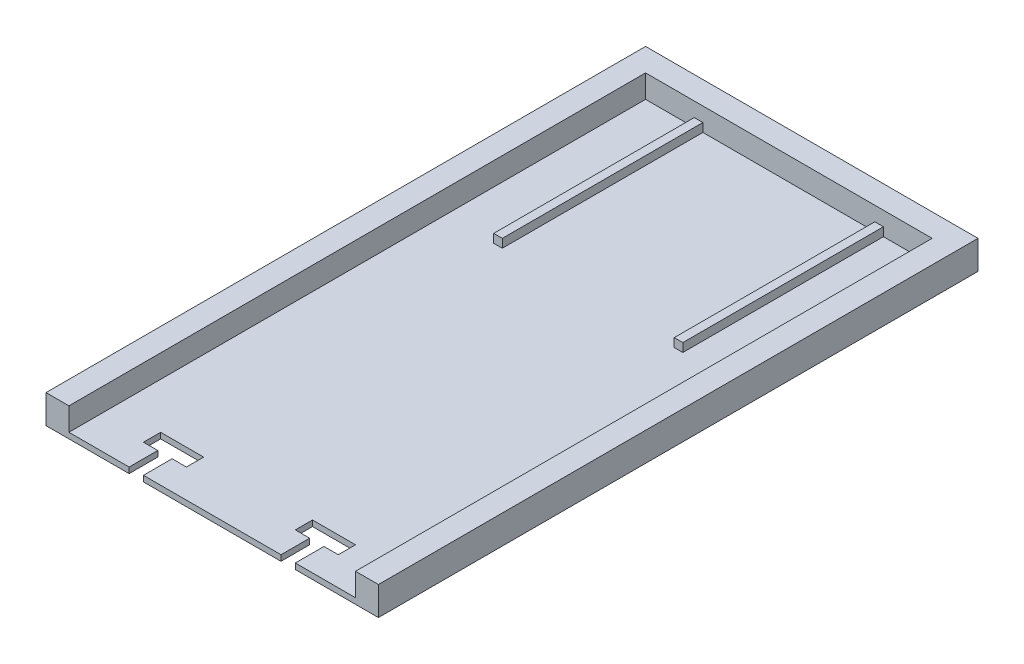
SolidWorks part; units mm, degrees
ref_plane "Front Plane" through (0, 0, 0) normal (0, 0, 1) x (1, 0, 0)
ref_plane "Top Plane" through (0, 0, 0) normal (0, 1, 0) x (1, 0, 0)
ref_plane "Right Plane" through (0, 0, 0) normal (1, 0, 0) x (0, 0, -1)
sketch "Sketch3" plane through (0, 0, 0) normal (0, 1, 0) x (1, 0, 0)
  line L0 (-1156.1049, 777.2674) -> (-1040.1049, 777.2674)
  line L1 (-1040.1049, 777.2674) -> (-1040.1049, 361.2674)
  line L2 (-1040.1049, 361.2674) -> (-1156.1049, 361.2674)
  line L3 (-1156.1049, 361.2674) -> (-1156.1049, 777.2674)
extrude "Boss-Extrude1" add sketch "Sketch3" along normal blind 10
sketch "Sketch4" plane through (0, 10, 0) normal (0, 1, 0) x (1, 0, 0)
  line L4 (-1148.1049, 769.2674) -> (-1048.1049, 769.2674)
  line L5 (-1148.1049, 769.2674) -> (-1148.1049, 369.2674)
  line L6 (-1148.1049, 369.2674) -> (-1048.1049, 369.2674)
  line L7 (-1048.1049, 769.2674) -> (-1048.1049, 369.2674)
  dimension "D1" = 100
  dimension "D2" = 400
extrude "Cut-Extrude1" cut sketch "Sketch4" against normal blind 8
sketch "Sketch6" plane through (0, 2, 0) normal (0, 1, 0) x (1, 0, 0)
  line L1 (-1048.1049, 769.2674) -> (-1148.1049, 769.2674) construction
  line L2 (-1128.1049, 769.2674) -> (-1128.1049, 669.2674)
  line L3 (-1128.1049, 669.2674) -> (-1131.1049, 669.2674)
  line L4 (-1131.1049, 669.2674) -> (-1131.1049, 769.2674)
  line L5 (-1128.1049, 769.2674) -> (-1131.1049, 769.2674)
  line L7 (-1068.1049, 769.2674) -> (-1068.1049, 669.2674)
  line L8 (-1068.1049, 669.2674) -> (-1065.1049, 669.2674)
  line L9 (-1065.1049, 669.2674) -> (-1065.1049, 769.2674)
  line L10 (-1048.1049, 769.2674) -> (-1148.1049, 769.2674) construction
  line L11 (-1068.1049, 769.2674) -> (-1065.1049, 769.2674)
extrude "Boss-Extrude4" add sketch "Sketch6" along normal blind 3
sketch "Sketch7" plane through (0, 2, 0) normal (0, 1, 0) x (1, 0, 0)
  line L0 (-1068.1049, 669.2674) -> (-1085.4049, 669.2674)
  line L1 (-1068.1049, 769.2674) -> (-1068.1049, 669.2674) construction
  line L2 (-1068.1049, 769.2674) -> (-1068.1049, 669.2674) construction
  circle A0 centre (-1085.4049, 452.1683) radius 1.5
extrude "Boss-Extrude5" add sketch "Sketch7" along normal blind 3 contours A0
sketch "Sketch8" plane through (0, 2, 0) normal (0, 1, 0) x (1, 0, 0)
  line L0 (-1040.1049, 361.2674) -> (-1040.1049, 538.0477)
  line L1 (-1040.1049, 361.2674) -> (-1040.1049, 777.2674) construction
  line L2 (-1040.1049, 538.0477) -> (-1156.1049, 538.0477)
  line L3 (-1156.1049, 777.2674) -> (-1156.1049, 361.2674) construction
  line L4 (-1156.1049, 538.0477) -> (-1156.1049, 361.2674)
  line L5 (-1156.1049, 361.2674) -> (-1040.1049, 361.2674) construction
  line L6 (-1156.1049, 361.2674) -> (-1040.1049, 361.2674)
extrude "Cut-Extrude2" cut sketch "Sketch8" against normal blind 10 and the other way blind 10
sketch "Sketch9" plane through (0, 2, 0) normal (0, 1, 0) x (1, 0, 0)
  line L0 (-1127.1049, 538.0477) -> (-1122.1049, 538.0477)
  line L1 (-1148.1049, 538.0477) -> (-1048.1049, 538.0477) construction
  line L2 (-1127.1049, 538.0477) -> (-1127.1049, 548.0477)
  line L3 (-1127.1049, 548.0477) -> (-1132.1049, 548.0477)
  line L4 (-1132.1049, 548.0477) -> (-1132.1049, 554.0477)
  line L6 (-1122.1049, 538.0477) -> (-1122.1049, 548.0477)
  line L7 (-1122.1049, 548.0477) -> (-1117.1049, 548.0477)
  line L8 (-1117.1049, 548.0477) -> (-1117.1049, 554.0477)
  line L9 (-1117.1049, 554.0477) -> (-1132.1049, 554.0477)
  line L10 (-1098.1049, 538.0477) -> (-1098.1049, 777.2674)
  line L11 (-1040.1049, 777.2674) -> (-1156.1049, 777.2674) construction
  line L12 (-1079.1049, 554.0477) -> (-1064.1049, 554.0477)
  line L13 (-1079.1049, 548.0477) -> (-1079.1049, 554.0477)
  line L14 (-1074.1049, 548.0477) -> (-1079.1049, 548.0477)
  line L15 (-1074.1049, 538.0477) -> (-1074.1049, 548.0477)
  line L16 (-1064.1049, 548.0477) -> (-1064.1049, 554.0477)
  line L17 (-1069.1049, 548.0477) -> (-1064.1049, 548.0477)
  line L18 (-1069.1049, 538.0477) -> (-1069.1049, 548.0477)
  line L19 (-1069.1049, 538.0477) -> (-1074.1049, 538.0477)
  line M2 (-1148.1049, 538.0477) -> (-1048.1049, 538.0477)
extrude "Cut-Extrude4" cut sketch "Sketch9" against normal blind 37 contours L8 L9 L4 L3 L2 L6 L7 M2 | L18 L17 L16 L12 L13 L14 L15 M2
sketch "Sketch10" plane through (0, 5, 0) normal (0, 1, 0) x (1, 0, 0)
  line L0 (-1156.1049, 538.0477) -> (-1156.1049, 568.0477)
  line L1 (-1156.1049, 777.2674) -> (-1156.1049, 538.0477) construction
  line L2 (-1069.1049, 568.0477) -> (-1074.1049, 568.0477)
  line L3 (-1040.1049, 538.0477) -> (-1040.1049, 777.2674) construction
  line L4 (-1079.1049, 584.0477) -> (-1064.1049, 584.0477)
  line L5 (-1127.1049, 568.0477) -> (-1127.1049, 578.0477)
  line L6 (-1127.1049, 578.0477) -> (-1132.1049, 578.0477)
  line L7 (-1132.1049, 578.0477) -> (-1132.1049, 584.0477)
  line L8 (-1079.1049, 578.0477) -> (-1079.1049, 584.0477)
  line L9 (-1122.1049, 568.0477) -> (-1122.1049, 578.0477)
  line L10 (-1122.1049, 578.0477) -> (-1117.1049, 578.0477)
  line L11 (-1117.1049, 578.0477) -> (-1117.1049, 584.0477)
  line L12 (-1117.1049, 584.0477) -> (-1132.1049, 584.0477)
  line L13 (-1156.1049, 568.0477) -> (-1040.1049, 568.0477)
  line L14 (-1156.1049, 568.0477) -> (-1156.1049, 538.0477)
  line L15 (-1040.1049, 538.0477) -> (-1040.1049, 568.0477)
  line L16 (-1156.1049, 538.0477) -> (-1040.1049, 538.0477)
  line L17 (-1074.1049, 578.0477) -> (-1079.1049, 578.0477)
  line L18 (-1127.1049, 568.0477) -> (-1122.1049, 568.0477)
  line L19 (-1074.1049, 568.0477) -> (-1074.1049, 578.0477)
  line L20 (-1064.1049, 578.0477) -> (-1064.1049, 584.0477)
  line L21 (-1069.1049, 578.0477) -> (-1064.1049, 578.0477)
  line L22 (-1069.1049, 568.0477) -> (-1069.1049, 578.0477)
extrude "Cut-Extrude5" cut sketch "Sketch10" against normal blind 10 contours L5 L13 L9 L10 L11 L12 L7 L6 | L0 L16 L15 L13 L2 | L2 L22 L21 L20 L4 L8 L17 L19
sketch "Sketch11" plane through (0, 0, 0) normal (0, 1, 0) x (1, 0, 0)
  line L0 (-1148.1049, 568.0477) -> (-1156.1049, 568.0477)
  line L1 (-1156.1049, 568.0477) -> (-1156.1049, 538.0477)
  line L2 (-1156.1049, 538.0477) -> (-1148.1049, 538.0477)
  line L3 (-1148.1049, 538.0477) -> (-1148.1049, 568.0477)
  line L4 (-1048.1049, 568.0477) -> (-1040.1049, 568.0477)
  line L5 (-1040.1049, 538.0477) -> (-1040.1049, 777.2674) construction
  line L6 (-1040.1049, 568.0477) -> (-1040.1049, 538.0477)
  line L7 (-1040.1049, 538.0477) -> (-1048.1049, 538.0477)
  line L8 (-1048.1049, 538.0477) -> (-1048.1049, 568.0477)
extrude "Cut-Extrude6" cut sketch "Sketch11" along normal blind 10 contours L3 L0 L1 L2 | L8 L4 L6 L7
sketch "Sketch12" plane through (0, 2, 0) normal (0, 1, 0) x (1, 0, 0)
  line L0 (-1068.1049, 669.2674) -> (-1065.1049, 669.2674)
  line L1 (-1065.1049, 669.2674) -> (-1065.1049, 699.2674)
  line L2 (-1065.1049, 669.2674) -> (-1065.1049, 769.2674) construction
  line L3 (-1068.1049, 669.2674) -> (-1068.1049, 699.2674)
  line L4 (-1068.1049, 699.2674) -> (-1065.1049, 699.2674)
extrude "Cut-Extrude7" cut sketch "Sketch12" along normal blind 10
sketch "Sketch13" plane through (0, 0, 0) normal (0, 1, 0) x (1, 0, 0)
  line L0 (-1131.1049, 669.2674) -> (-1128.1049, 669.2674)
  line L8 (-1128.1049, 669.2674) -> (-1128.1049, 699.2674)
  line L9 (-1128.1049, 669.2674) -> (-1128.1049, 769.2674) construction
  line L10 (-1128.1049, 699.2674) -> (-1131.1049, 699.2674)
  line L11 (-1131.1049, 699.2674) -> (-1131.1049, 669.2674)
extrude "Cut-Extrude10" cut sketch "Sketch13" along normal blind 14
sketch "Sketch14" plane through (0, 0, 0) normal (0, 1, 0) x (1, 0, 0)
  line L0 (-1131.1049, 699.2674) -> (-1128.1049, 699.2674)
  line L1 (-1128.1049, 699.2674) -> (-1128.1049, 669.2674)
  line L2 (-1128.1049, 669.2674) -> (-1131.1049, 669.2674)
  line L3 (-1131.1049, 669.2674) -> (-1131.1049, 699.2674) construction
  line L4 (-1131.1049, 669.2674) -> (-1131.1049, 699.2674)
extrude "Boss-Extrude8" add sketch "Sketch14" along normal blind 2
